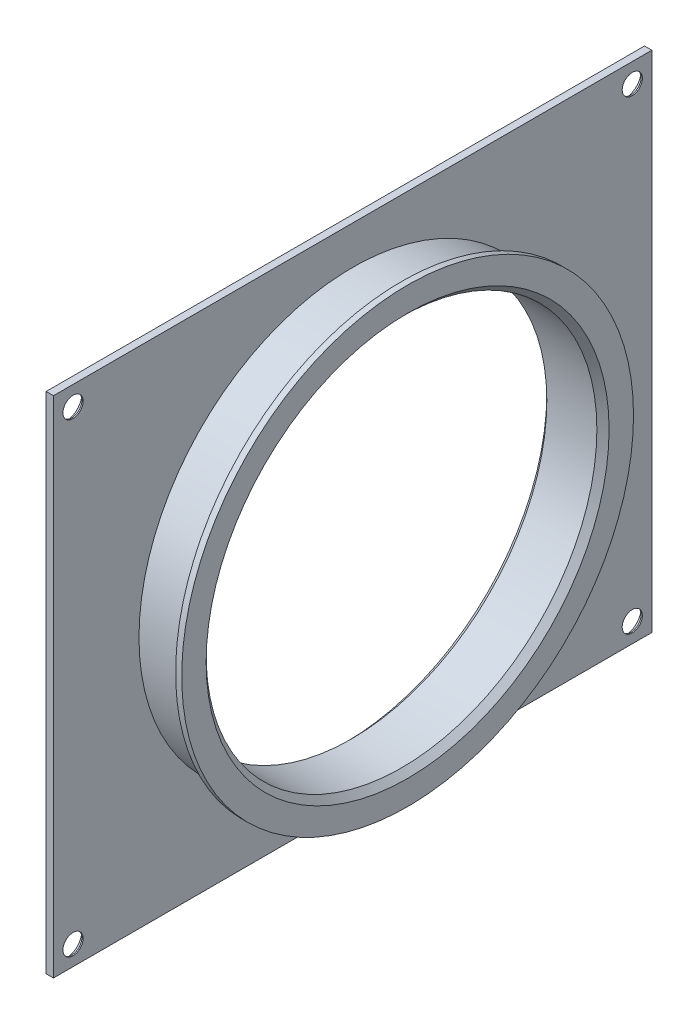
SolidWorks part; units mm, degrees
ref_plane "Front Plane" through (0, 0, 0) normal (1, 0, 0) x (0, 1, 0)
ref_plane "Top Plane" through (0, 0, 0) normal (0, 0, 1) x (0, 1, 0)
ref_plane "Right Plane" through (0, 0, 0) normal (0, 1, 0) x (-1, 0, 0)
sketch "Sketch1" plane through (0, 0, 0) normal (1, 0, 0) x (0, 1, 0)
  line L1 (0, 0) -> (82.6, 0)
  line L2 (0, 0) -> (0, 98)
  line L3 (0, 98) -> (82.6, 98)
  line L4 (82.6, 0) -> (82.6, 98)
  dimension "D1" = 98
  dimension "D2" = 82.6
extrude "Boss-Extrude1" add sketch "Sketch1" along normal blind 1.2
sketch "Sketch2" plane through (1.2, 0, 0) normal (1, 0, 0) x (0, 1, 0)
  line L0 (0, 0) -> (82.6, 0) construction
  line L1 (3.2, 94.8) -> (79.4, 94.8) construction
  line L2 (3.2, 94.8) -> (3.2, 3.2) construction
  line L3 (3.2, 3.2) -> (79.4, 3.2) construction
  line L4 (79.4, 94.8) -> (79.4, 3.2) construction
  line L5 (0, 98) -> (0, 0) construction
  circle A0 centre (3.2, 94.8) radius 1.65
  circle A1 centre (79.4, 94.8) radius 1.65
  circle A2 centre (3.2, 3.2) radius 1.65
  circle A3 centre (79.4, 3.2) radius 1.65
  dimension "D5" = 3.3
  dimension "D1" = 91.6
  dimension "D2" = 76.2
  dimension "D3" = 3.2
  dimension "D4" = 3.2
extrude "Cut-Extrude1" cut sketch "Sketch2" against normal through all
sketch "Sketch3" plane through (1.2, 0, 0) normal (1, 0, 0) x (0, 1, 0)
  line L0 (0, 98) -> (82.6, 0) construction
  line L1 (0, 0) -> (82.6, 98) construction
  circle A0 centre (41.3, 49) radius 35
  dimension "D1" = 70
extrude "Boss-Extrude2" add sketch "Sketch3" along normal blind 8
sketch "Sketch4" plane through (9.2, 0, 0) normal (1, 0, 0) x (0, 1, 0)
  circle A0 centre (41.3, 49) radius 37
  circle A1 centre (41.3, 49) radius 35 construction
  dimension "D1" = 74
extrude "Boss-Extrude3" add sketch "Sketch4" along normal blind 1 contours A0
sketch "Sketch5" plane through (10.2, 0, 0) normal (1, 0, 0) x (0, 1, 0)
  circle A0 centre (41.3, 49) radius 32
  circle A2 centre (41.3, 49) radius 37 construction
  dimension "D1" = 64
extrude "Cut-Extrude2" cut sketch "Sketch5" against normal through all contours A0
chamfer "Chamfer1" distance 1 angle 45 6 edges at (0, 79.4, 93.15) (0, 79.4, 1.55) (0, 3.2, 1.55) (0, 3.2, 93.15) (10.2, 41.3, 17) (0, 41.3, 17)
